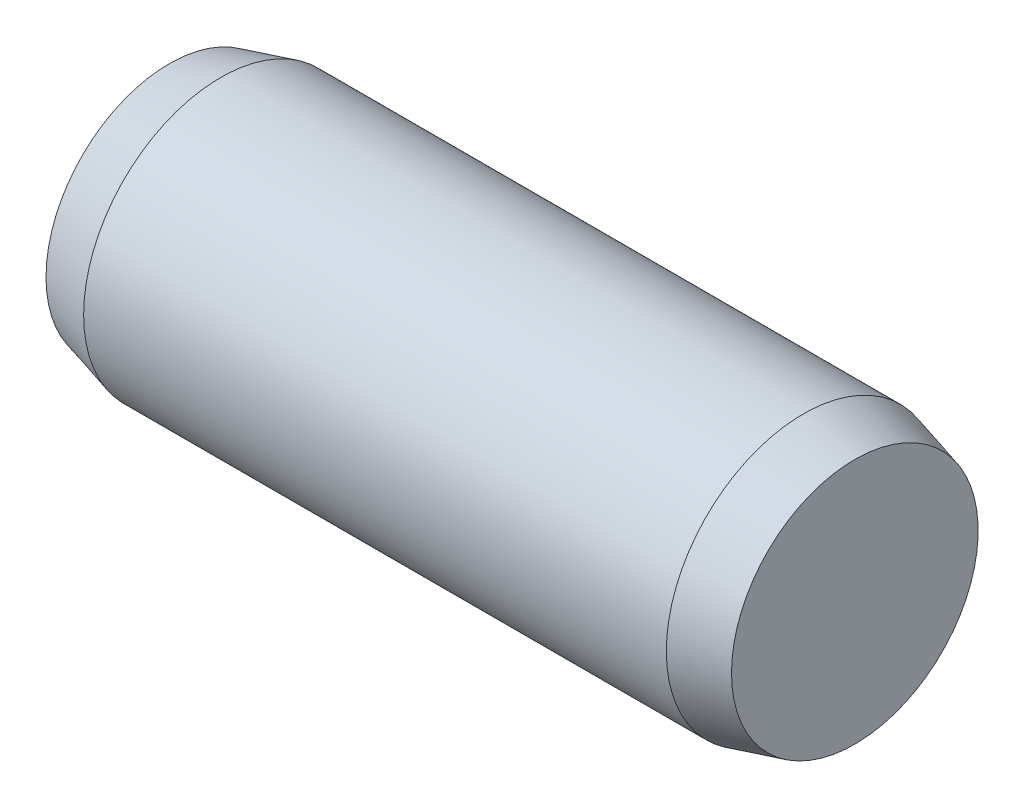
SolidWorks part; units mm, degrees
material "Stahl"
ref_plane "Plane1" through (0, 0, 0) normal (0, 0, 1) x (1, 0, 0)
ref_plane "Plane2" through (0, 0, 0) normal (0, 1, 0) x (1, 0, 0)
ref_plane "Plane3" through (0, 0, 0) normal (1, 0, 0) x (0, 0, -1)
sketch "Sketch1" plane through (0, 0, 0) normal (0, 0, 1) x (1, 0, 0)
  line L1 (-6.35, 0) -> (107.95, 0) construction
  line L2 (0, 0) -> (40, 0)
  line L3 (40, 0) -> (40, 7.1962)
  line L4 (40, 7.1962) -> (37, 8)
  line L5 (37, 8) -> (3, 8)
  line L6 (0, 7.1962) -> (0, 0)
  line L7 (0, 7.1962) -> (3, 8)
  dimension "Chamfer_len" = 3
  dimension "D3" = 15
  dimension "Diameter" = 16
  dimension "D1" = 3
  dimension "D2" = 15
  dimension "Length" = 40
revolve "Base-Revolve" add sketch "Sketch1" angle 360 about L1
equation "\"D3@Sketch1\" = 15.0"
equation "\"D1@Sketch1\" = \"Chamfer_len@Sketch1\""
equation "\"D2@Sketch1\" = \"D3@Sketch1\""
